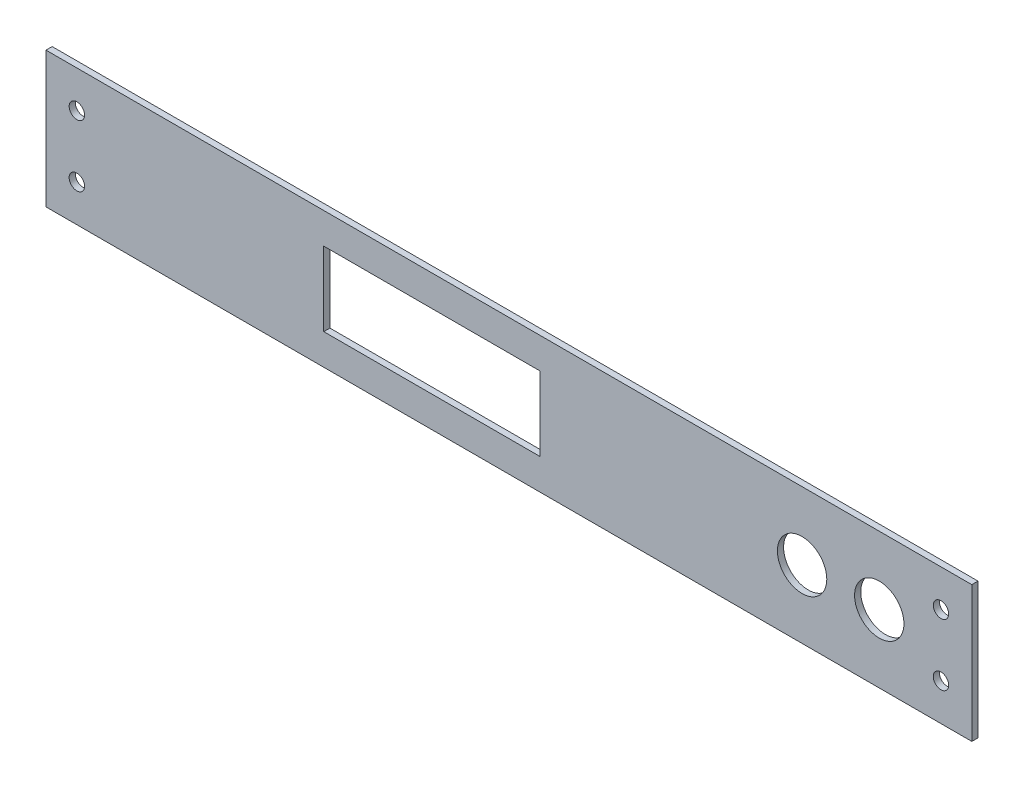
SolidWorks part; units mm, degrees
material "ABS"
ref_plane "Plano frontal" through (0, 0, 0) normal (0, 0, 1) x (1, 0, 0)
ref_plane "Plano superior" through (0, 0, 0) normal (0, 1, 0) x (1, 0, 0)
ref_plane "Plano direito" through (0, 0, 0) normal (1, 0, 0) x (0, 0, -1)
sketch "Esboço1" plane through (0, 0, 0) normal (0, 0, 1) x (1, 0, 0)
  line L0 (-64.0948, 22.6335) -> (235.9052, 22.6335)
  line L2 (-64.0948, 22.6335) -> (-64.0948, -21.3665)
  line L3 (-64.0948, -21.3665) -> (235.9052, -21.3665)
  line L4 (235.9052, 22.6335) -> (235.9052, -21.3665)
  line L6 (25.9052, -11.3665) -> (95.9052, -11.3665)
  line L7 (25.9052, -11.3665) -> (25.9052, 12.6335)
  line L8 (25.9052, 12.6335) -> (95.9052, 12.6335)
  line L9 (95.9052, 12.6335) -> (95.9052, -11.3665)
  circle A0 centre (-54.0948, 10.6335) radius 2.5
  circle A1 centre (-54.0948, -9.3665) radius 2.5
  circle A2 centre (225.9052, 10.6335) radius 2.5
  circle A3 centre (225.9052, -9.3665) radius 2.5
  circle A4 centre (205.9052, 0.6335) radius 8
  circle A5 centre (180.9052, 0.6335) radius 8
  dimension "D5" = 5
  dimension "D8" = 5
  dimension "D11" = 5
  dimension "D12" = 5
  dimension "D9" = 16
  dimension "D13" = 16
  dimension "D1" = 300
  dimension "D2" = 44
  dimension "D6" = 70
  dimension "D7" = 24
  dimension "D10" = 25
extrude "Ressalto-extrusão1" add sketch "Esboço1" along normal blind 2
